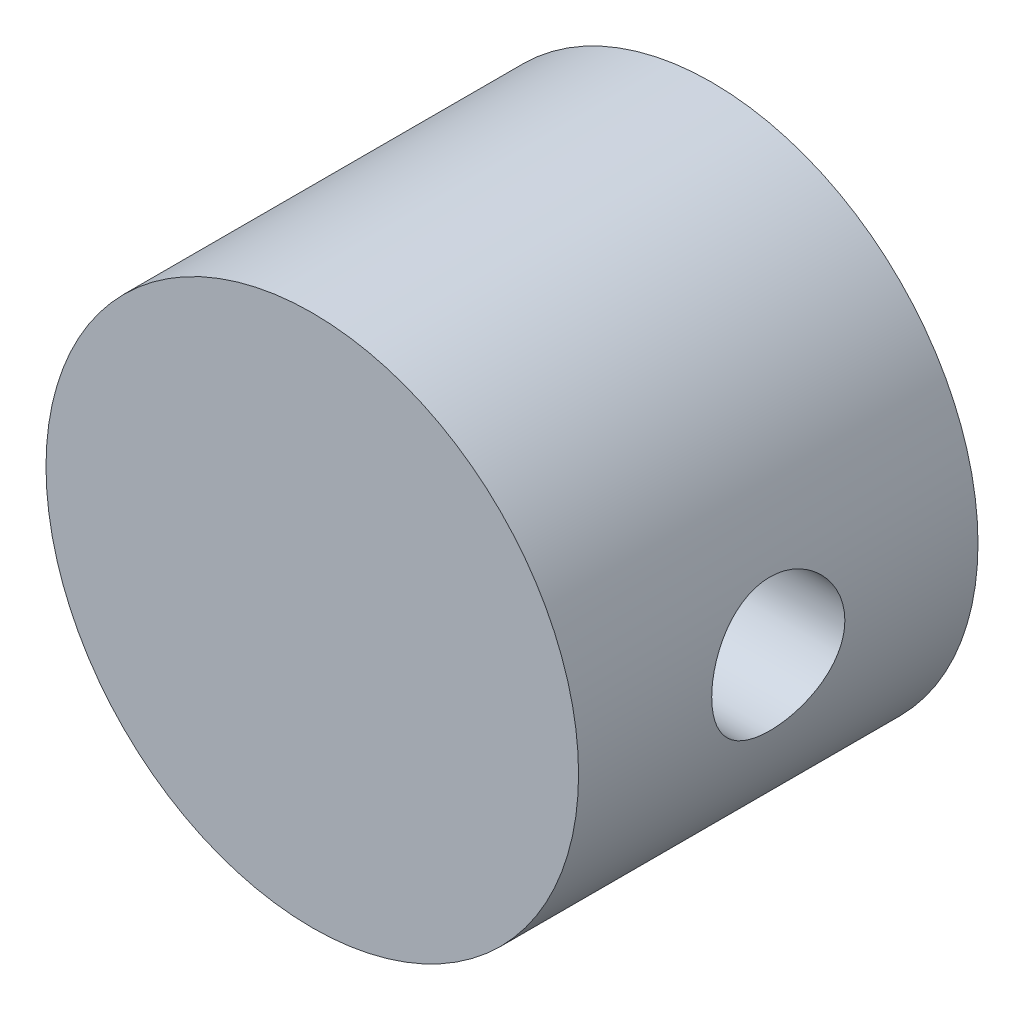
SolidWorks part; units mm, degrees
ref_plane "Front Plane" through (0, 0, 0) normal (0, 0, 1) x (1, 0, 0)
ref_plane "Top Plane" through (0, 0, 0) normal (0, 1, 0) x (1, 0, 0)
ref_plane "Right Plane" through (0, 0, 0) normal (1, 0, 0) x (0, 0, -1)
sketch "Sketch1" plane through (0, 0, 0) normal (0, 0, 1) x (1, 0, 0)
  line L1 (-22.674, 12.1545) -> (-6.674, 12.1545)
  line L2 (-22.674, 12.1545) -> (-22.674, -3.8455)
  line L3 (-22.674, -3.8455) -> (-6.674, -3.8455)
  line L4 (-6.674, 12.1545) -> (-6.674, -3.8455)
  dimension "D1" = 16
extrude "Boss-Extrude1" add sketch "Sketch1" along normal blind 12
sketch "Sketch2" plane through (-6.674, 0, 0) normal (1, 0, 0) x (0, 0, -1)
  line L0 (-12, 12.1545) -> (0, 12.1545) construction
  line L1 (0, -3.8455) -> (0, 12.1545) construction
  circle A0 centre (-6, 4.1545) radius 2
  point P6 (-6, 12.1545)
  point P9 (0, 4.1545)
  dimension "D1" = 4
sketch "Sketch3" plane through (0, 0, 12) normal (0, 0, 1) x (1, 0, 0)
  line L0 (-6.674, 12.1545) -> (-22.674, 12.1545) construction
  line L1 (-6.674, -3.8455) -> (-6.674, 12.1545) construction
  line L3 (-22.674, 12.1545) -> (-6.674, 12.1545)
  line L4 (-22.674, 12.1545) -> (-22.674, -3.8455)
  line L5 (-22.674, -3.8455) -> (-6.674, -3.8455)
  line L6 (-6.674, 12.1545) -> (-6.674, -3.8455)
  circle A0 centre (-14.674, 4.1545) radius 8
  line M2 (-22.674, 12.1545) -> (-22.674, -3.8455)
  line M3 (-22.674, -3.8455) -> (-6.674, -3.8455)
  line M4 (-6.674, -3.8455) -> (-6.674, 12.1545)
  line M5 (-6.674, 12.1545) -> (-22.674, 12.1545)
  dimension "D1" = 16
extrude "Cut-Extrude1" cut sketch "Sketch3" against normal blind 13 contours A0 L6 M5 | A0 L5 M4 | A0 L3 M2 | A0 L4 M3
extrude "Cut-Extrude2" cut sketch "Sketch2" against normal blind 10
